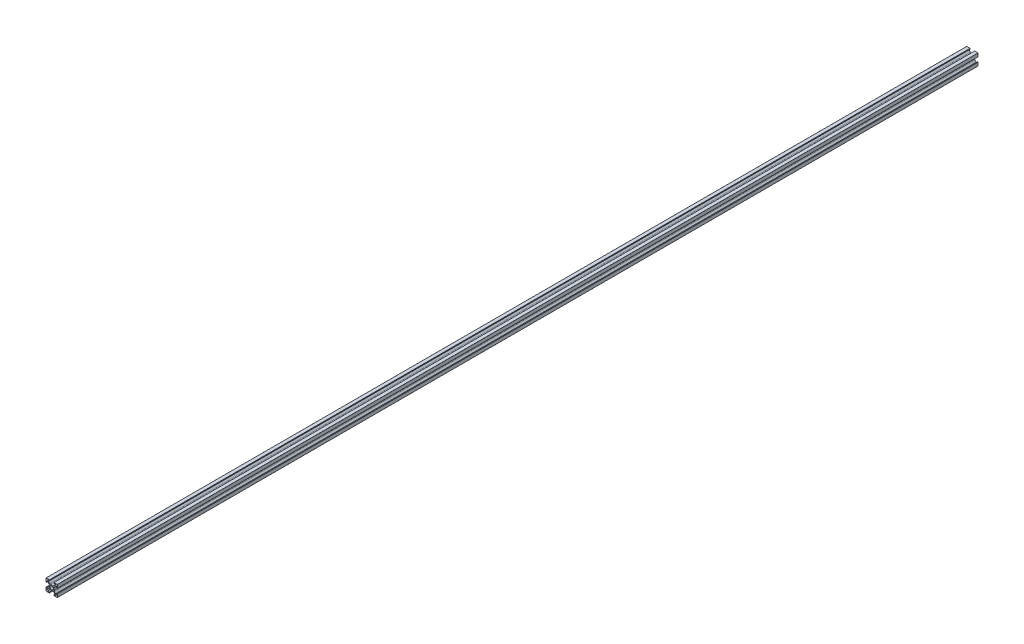
SolidWorks part; units mm, degrees
material "6061-T6 (SS)"
ref_plane "Front Plane" through (0, 0, 0) normal (0, 0, 1) x (1, 0, 0)
ref_plane "Top Plane" through (0, 0, 0) normal (0, 1, 0) x (1, 0, 0)
ref_plane "Right Plane" through (0, 0, 0) normal (1, 0, 0) x (0, 0, -1)
ref_plane "Plane1" through (0, 0, 60) normal (0, 0, 1) x (1, 0, 0)
sketch "Sketch1" plane through (0, 0, 60) normal (0, 0, 1) x (1, 0, 0)
  line L0 (18.5, 17.0086) -> (18.5, 14.1)
  line L1 (18.6, 14) -> (19.9, 14)
  line L2 (20, 14.1) -> (20, 19.9)
  line L3 (19.9, 20) -> (14.1, 20)
  line L4 (14, 19.9) -> (14, 18.6)
  line L5 (14.1, 18.5) -> (17.0086, 18.5)
  line L6 (17.0793, 18.3293) -> (13.3358, 14.5858)
  line L7 (11.9216, 14) -> (8.0784, 14)
  line L8 (6.6642, 14.5858) -> (2.9207, 18.3293)
  line L9 (2.9914, 18.5) -> (5.9, 18.5)
  line L10 (6, 18.6) -> (6, 19.9)
  line L11 (5.9, 20) -> (0.1, 20)
  line L12 (0, 19.9) -> (0, 14.1)
  line L13 (0.1, 14) -> (1.4, 14)
  line L14 (1.5, 14.1) -> (1.5, 17.0086)
  line L15 (1.6707, 17.0793) -> (5.4142, 13.3358)
  line L16 (6, 11.9216) -> (6, 8.0784)
  line L17 (5.4142, 6.6642) -> (1.6707, 2.9207)
  line L18 (1.5, 2.9914) -> (1.5, 5.9)
  line L19 (1.4, 6) -> (0.1, 6)
  line L20 (0, 5.9) -> (0, 0.1)
  line L21 (0.1, 0) -> (5.9, 0)
  line L22 (6, 0.1) -> (6, 1.4)
  line L23 (5.9, 1.5) -> (2.9914, 1.5)
  line L24 (2.9207, 1.6707) -> (6.6642, 5.4142)
  line L25 (8.0784, 6) -> (11.9216, 6)
  line L26 (13.3358, 5.4142) -> (17.0793, 1.6707)
  line L27 (17.0086, 1.5) -> (14.1, 1.5)
  line L28 (14, 1.4) -> (14, 0.1)
  line L29 (14.1, 0) -> (19.9, 0)
  line L30 (20, 0.1) -> (20, 5.9)
  line L31 (19.9, 6) -> (18.6, 6)
  line L32 (18.5, 5.9) -> (18.5, 2.9914)
  line L33 (18.3293, 2.9207) -> (14.5858, 6.6642)
  line L34 (14, 8.0784) -> (14, 11.9216)
  line L35 (14.5858, 13.3358) -> (18.3293, 17.0793)
  circle A0 centre (10, 10) radius 3
  arc A1 (18.3293, 17.0793) -> (18.5, 17.0086) centre (18.4, 17.0086) cw
  arc A2 (18.5, 14.1) -> (18.6, 14) centre (18.6, 14.1) ccw
  arc A3 (19.9, 14) -> (20, 14.1) centre (19.9, 14.1) ccw
  arc A4 (20, 19.9) -> (19.9, 20) centre (19.9, 19.9) ccw
  arc A5 (14.1, 20) -> (14, 19.9) centre (14.1, 19.9) ccw
  arc A6 (14, 18.6) -> (14.1, 18.5) centre (14.1, 18.6) ccw
  arc A7 (17.0086, 18.5) -> (17.0793, 18.3293) centre (17.0086, 18.4) cw
  arc A8 (13.3358, 14.5858) -> (11.9216, 14) centre (11.9216, 16) cw
  arc A9 (8.0784, 14) -> (6.6642, 14.5858) centre (8.0784, 16) cw
  arc A10 (2.9207, 18.3293) -> (2.9914, 18.5) centre (2.9914, 18.4) cw
  arc A11 (5.9, 18.5) -> (6, 18.6) centre (5.9, 18.6) ccw
  arc A12 (6, 19.9) -> (5.9, 20) centre (5.9, 19.9) ccw
  arc A13 (0.1, 20) -> (0, 19.9) centre (0.1, 19.9) ccw
  arc A14 (0, 14.1) -> (0.1, 14) centre (0.1, 14.1) ccw
  arc A15 (1.4, 14) -> (1.5, 14.1) centre (1.4, 14.1) ccw
  arc A16 (1.5, 17.0086) -> (1.6707, 17.0793) centre (1.6, 17.0086) cw
  arc A17 (5.4142, 13.3358) -> (6, 11.9216) centre (4, 11.9216) cw
  arc A18 (6, 8.0784) -> (5.4142, 6.6642) centre (4, 8.0784) cw
  arc A19 (1.6707, 2.9207) -> (1.5, 2.9914) centre (1.6, 2.9914) cw
  arc A20 (1.5, 5.9) -> (1.4, 6) centre (1.4, 5.9) ccw
  arc A21 (0.1, 6) -> (0, 5.9) centre (0.1, 5.9) ccw
  arc A22 (0, 0.1) -> (0.1, 0) centre (0.1, 0.1) ccw
  arc A23 (5.9, 0) -> (6, 0.1) centre (5.9, 0.1) ccw
  arc A24 (6, 1.4) -> (5.9, 1.5) centre (5.9, 1.4) ccw
  arc A25 (2.9914, 1.5) -> (2.9207, 1.6707) centre (2.9914, 1.6) cw
  arc A26 (6.6642, 5.4142) -> (8.0784, 6) centre (8.0784, 4) cw
  arc A27 (11.9216, 6) -> (13.3358, 5.4142) centre (11.9216, 4) cw
  arc A28 (17.0793, 1.6707) -> (17.0086, 1.5) centre (17.0086, 1.6) cw
  arc A29 (14.1, 1.5) -> (14, 1.4) centre (14.1, 1.4) ccw
  arc A30 (14, 0.1) -> (14.1, 0) centre (14.1, 0.1) ccw
  arc A31 (19.9, 0) -> (20, 0.1) centre (19.9, 0.1) ccw
  arc A32 (20, 5.9) -> (19.9, 6) centre (19.9, 5.9) ccw
  arc A33 (18.6, 6) -> (18.5, 5.9) centre (18.6, 5.9) ccw
  arc A34 (18.5, 2.9914) -> (18.3293, 2.9207) centre (18.4, 2.9914) cw
  arc A35 (14.5858, 6.6642) -> (14, 8.0784) centre (16, 8.0784) cw
  arc A36 (14, 11.9216) -> (14.5858, 13.3358) centre (16, 11.9216) cw
extrude "Boss-Extrude2" add sketch "Sketch1" along normal blind 1620
